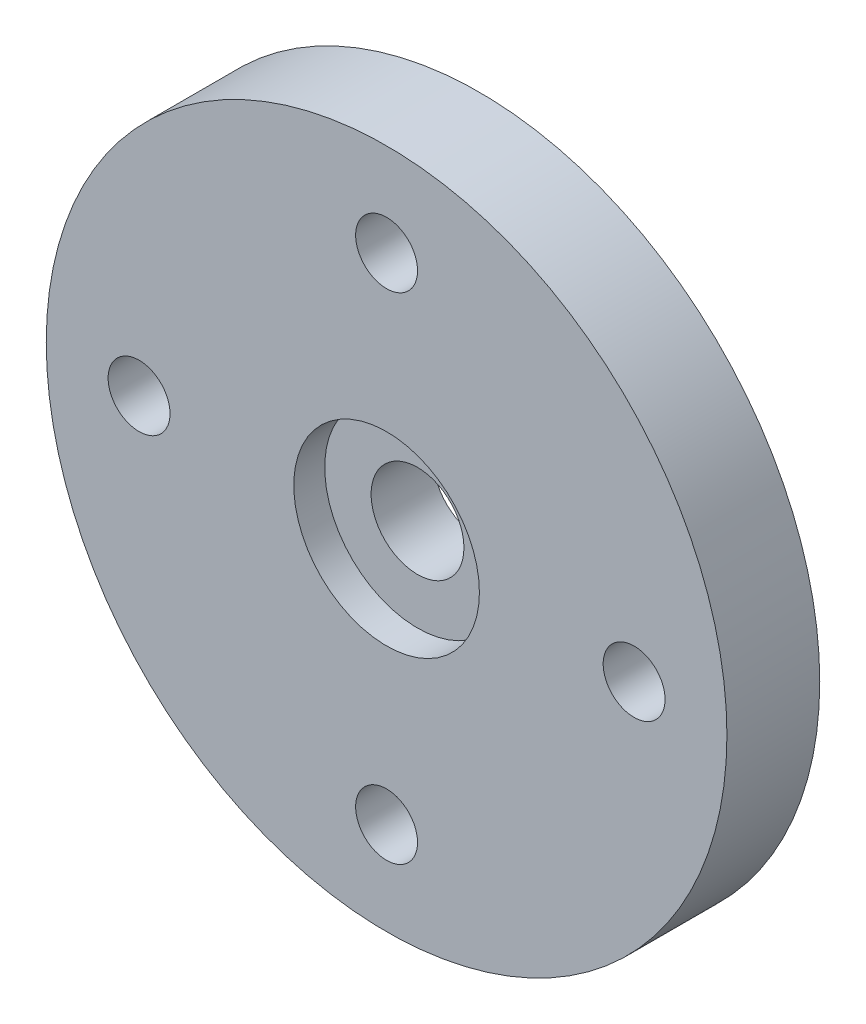
SolidWorks part; units mm, degrees
material "Stop 1060"
ref_plane "Płaszczyzna przednia" through (0, 0, 0) normal (0, 0, 1) x (1, 0, 0)
ref_plane "Płaszczyzna górna" through (0, 0, 0) normal (0, 1, 0) x (1, 0, 0)
ref_plane "Płaszczyzna prawa" through (0, 0, 0) normal (1, 0, 0) x (0, 0, -1)
sketch "Szkic1" plane through (0, 0, 0) normal (0, 0, 1) x (1, 0, 0)
  circle A0 centre (0, 0) radius 11
  circle A1 centre (0, 0) radius 8 construction
  circle A2 centre (0, 8) radius 1
  circle A3 centre (8, 0) radius 1
  circle A4 centre (0, -8) radius 1
  circle A5 centre (-8, 0) radius 1
  circle A6 centre (0, 0) radius 1.5
  point P15 (0, 0)
  dimension "D1" = 22
  dimension "D2" = 16
  dimension "D3" = 2
  dimension "D4" = 4
extrude "Dodanie-wyciągnięcie1" add sketch "Szkic1" along normal blind 3
sketch "Szkic2" plane through (0, 0, 3) normal (0, 0, 1) x (1, 0, 0)
  circle A0 centre (0, 0) radius 3
  dimension "D1" = 6
extrude "Wytnij-wyciągnięcie1" cut sketch "Szkic2" against normal blind 1
